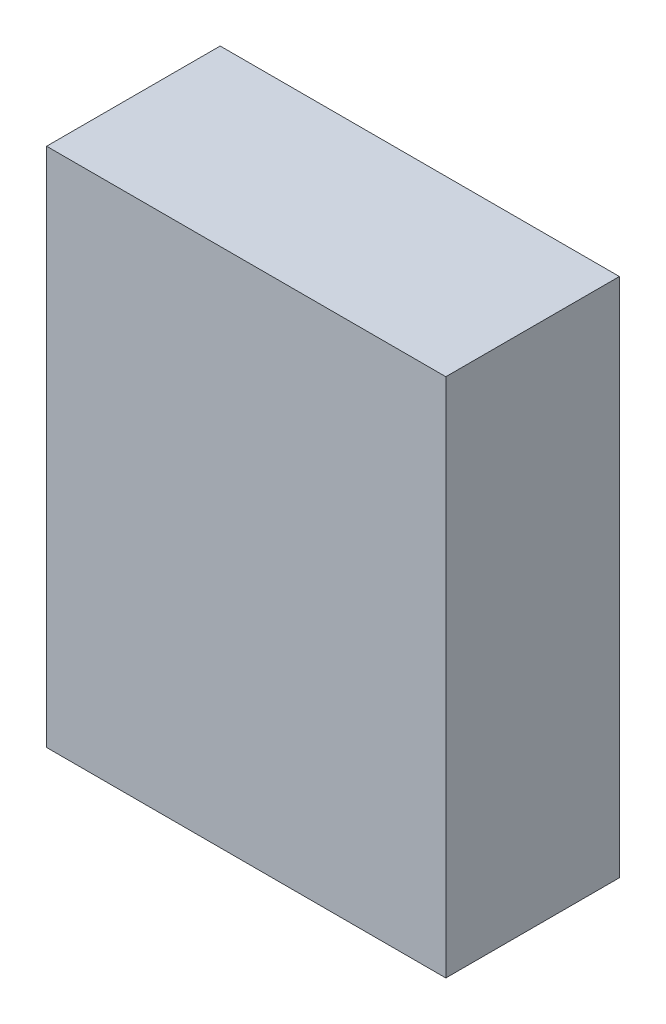
SolidWorks part; units mm, degrees
ref_plane "Plan de face" through (0, 0, 0) normal (0, 0, 1) x (1, 0, 0)
ref_plane "Plan de dessus" through (0, 0, 0) normal (0, 1, 0) x (1, 0, 0)
ref_plane "Plan de droite" through (0, 0, 0) normal (1, 0, 0) x (0, 0, -1)
sketch "Esquisse1" plane through (0, 0, 0) normal (0, 0, 1) x (1, 0, 0)
  line L1 (-48.4818, 22.1003) -> (66.5182, 22.1003)
  line L2 (-48.4818, 22.1003) -> (-48.4818, -127.8997)
  line L3 (-48.4818, -127.8997) -> (66.5182, -127.8997)
  line L4 (66.5182, 22.1003) -> (66.5182, -127.8997)
  dimension "D1" = 115
  dimension "D2" = 150
extrude "Boss.-Extru.1" add sketch "Esquisse1" along normal blind 50
